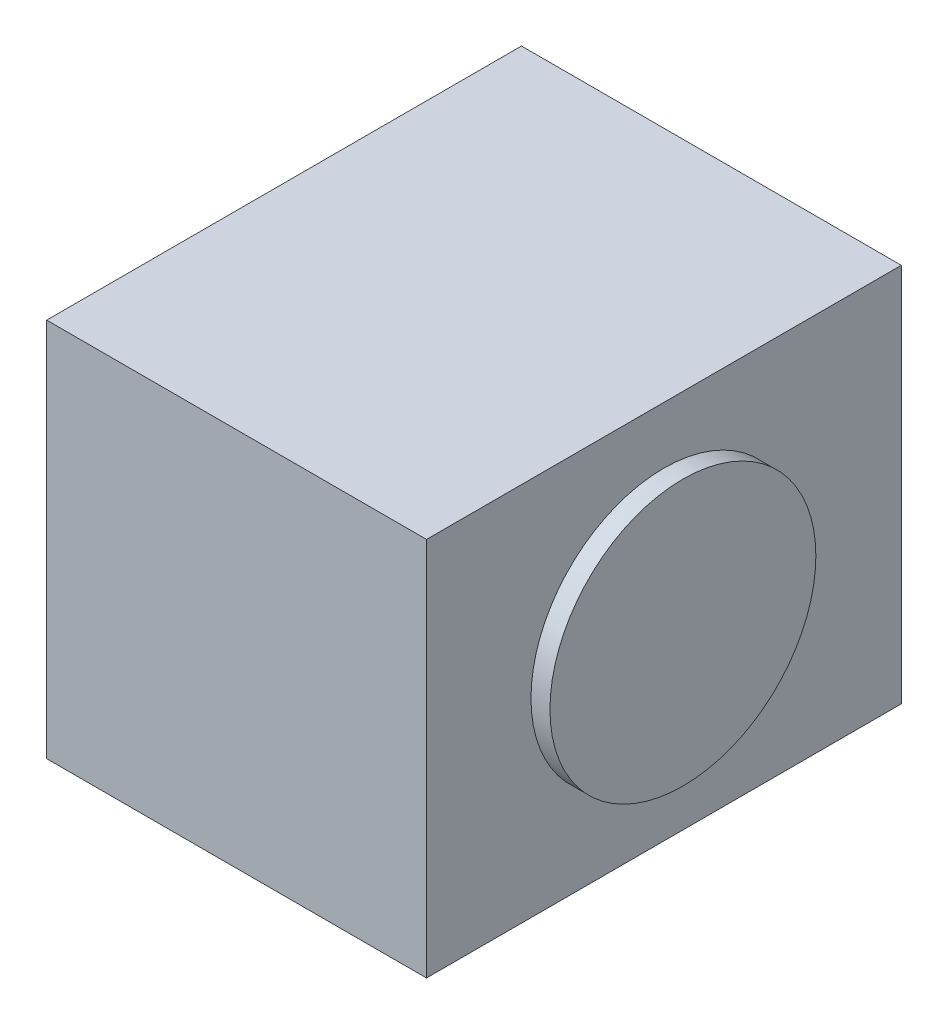
SolidWorks part; units mm, degrees
ref_plane "Plan de face" through (0, 0, 0) normal (0, 0, 1) x (1, 0, 0)
ref_plane "Plan de dessus" through (0, 0, 0) normal (0, 1, 0) x (1, 0, 0)
ref_plane "Plan de droite" through (0, 0, 0) normal (1, 0, 0) x (0, 0, -1)
sketch "Esquisse1" plane through (0, 0, 0) normal (0, 0, 1) x (1, 0, 0)
  line L1 (0, 0) -> (-200, 0)
  line L2 (0, 0) -> (0, -200)
  line L3 (0, -200) -> (-200, -200)
  line L4 (-200, 0) -> (-200, -200)
  dimension "D1" = 200
  dimension "D2" = 200
extrude "Boss.-Extru.1" add sketch "Esquisse1" along normal blind 250
sketch "Esquisse2" plane through (0, 0, 0) normal (0, 0, -1) x (-1, 0, 0)
  line L0 (200, -200) -> (0, -200) construction
  line L2 (200, 0) -> (200, -200) construction
  circle A0 centre (100, -100) radius 70
  point P8 (100, -100)
  dimension "D3" = 140
  dimension "D1" = 100
  dimension "D2" = 100
extrude "Enlèv. mat.-Extru.1" cut sketch "Esquisse2" against normal blind 10
sketch "Esquisse3" plane through (0, 0, 0) normal (1, 0, 0) x (0, 0, -1)
  line L0 (-250, -200) -> (-250, 0) construction
  line L2 (-250, -200) -> (0, -200) construction
  circle A0 centre (-125, -100) radius 70
  dimension "D1" = 140
  dimension "D2" = 125
  dimension "D3" = 100
extrude "Boss.-Extru.2" add sketch "Esquisse3" along normal blind 10
